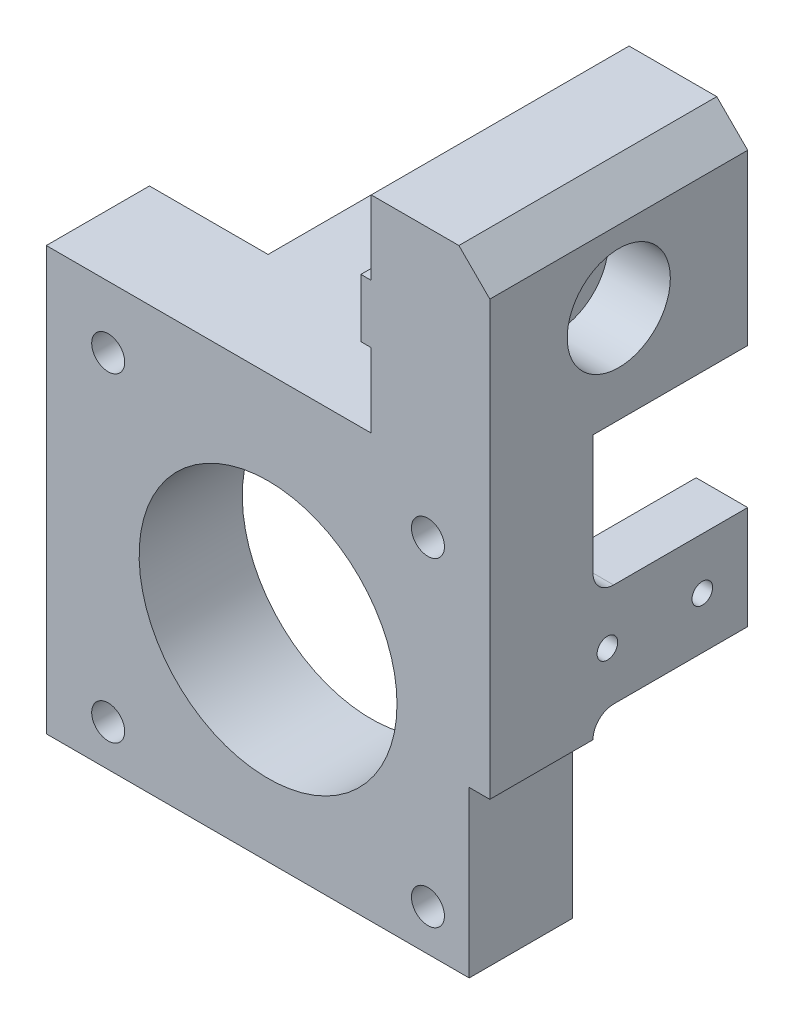
SolidWorks part; units mm, degrees
ref_plane "Plano frontal" through (0, 0, 0) normal (0, 0, 1) x (1, 0, 0)
ref_plane "Plano superior" through (0, 0, 0) normal (0, 1, 0) x (1, 0, 0)
ref_plane "Plano direito" through (0, 0, 0) normal (1, 0, 0) x (0, 0, -1)
sketch "Esboço1" plane through (0, 0, 0) normal (0, 0, 1) x (1, 0, 0)
  line L0 (-21.5, 21.5) -> (-21.5, -21.5)
  line L1 (-21.5, -21.5) -> (21.5, -21.5)
  line L2 (21.5, -21.5) -> (21.5, 38.5)
  line L3 (21.5, 38.5) -> (18.5, 41.5)
  line L4 (18.5, 41.5) -> (10, 41.5)
  line L5 (10, 41.5) -> (10, 34.325)
  line L6 (10, 34.325) -> (9, 34.325)
  line L7 (9, 34.325) -> (9, 28.675)
  line L8 (9, 28.675) -> (10, 28.675)
  line L9 (10, 28.675) -> (10, 21.5)
  line L10 (10, 21.5) -> (-21.5, 21.5)
  line L11 (0, -21.5) -> (0, 0) construction
  line L12 (-21.5, 0) -> (0, 0) construction
  line L13 (9, 31.5) -> (21.5, 31.5) construction
  line L14 (14.25, 41.5) -> (14.25, 21.5) construction
  line L15 (10, 21.5) -> (21.5, 21.5) construction
  line L17 (15.5, -15.5) -> (-15.5, -15.5) construction
  line L18 (15.5, -15.5) -> (15.5, 15.5) construction
  line L19 (15.5, 15.5) -> (-15.5, 15.5) construction
  line L20 (-15.5, -15.5) -> (-15.5, 15.5) construction
  line L21 (15.5, -15.5) -> (-15.5, 15.5) construction
  line L22 (15.5, 15.5) -> (-15.5, -15.5) construction
  circle A0 centre (0, 0) radius 12.5
  circle A1 centre (-15.5, 15.5) radius 1.6
  circle A2 centre (15.5, 15.5) radius 1.6
  circle A3 centre (15.5, -15.5) radius 1.6
  circle A4 centre (-15.5, -15.5) radius 1.6
  point P20 (14.25, 31.5)
  dimension "D10" = 25
  dimension "D9" = 3.2
  dimension "D1" = 43
  dimension "D2" = 43
  dimension "D3" = 60
  dimension "D4" = 11.5
  dimension "D5" = 135
  dimension "D6" = 20
  dimension "D7" = 5.65
  dimension "D8" = 1
  dimension "D11" = 31
  dimension "D12" = 31
extrude "Ressalto-extrusão1" add sketch "Esboço1" along normal blind 10
sketch "Esboço3" plane through (0, 0, 0) normal (0, 0, -1) x (-1, 0, 0)
  circle A0 centre (-15.5, 15.5) radius 3.6
  circle A1 centre (15.5, 15.5) radius 3.6
  circle A2 centre (15.5, -15.5) radius 3.6
  circle A3 centre (-15.5, -15.5) radius 3.6
  dimension "D1" = 7.2
extrude "Corte-extrusão1" cut sketch "Esboço3" against normal blind 3
sketch "Esboço2" plane through (0, 0, 0) normal (0, 0, -1) x (-1, 0, 0)
  line L0 (-18.5, 41.5) -> (-21.5, 38.5)
  line L1 (-21.5, 38.5) -> (-21.5, 22.1)
  line L4 (10, 15.5) -> (10, 21.5)
  line L5 (-10, 21.5) -> (21.5, 21.5) construction
  line L6 (10, 21.5) -> (-10, 21.5)
  line L7 (-10, 21.5) -> (-10, 28.675)
  line L8 (-10, 28.675) -> (-9, 28.675)
  line L9 (-9, 28.675) -> (-9, 34.325)
  line L10 (-9, 34.325) -> (-10, 34.325)
  line L11 (-10, 34.325) -> (-10, 41.5)
  line L12 (-10, 41.5) -> (-18.5, 41.5)
  line L13 (7, 12.5) -> (10, 15.5)
  line L14 (-10.9, 12.5) -> (7, 12.5)
  line L15 (-21.5, 22.1) -> (-18.5, 19.1)
  line L16 (-18.5, 19.1) -> (-15.5, 19.1)
  line L17 (-11.9, 15.5) -> (-11.9, 13.5)
  line L18 (-11.9, 13.5) -> (-10.9, 12.5)
  circle A1 centre (-15.5, 15.5) radius 3.6 construction
  arc A2 (-11.9, 15.5) -> (-15.5, 19.1) centre (-15.5, 15.5) ccw
  circle A3 centre (0, 0) radius 12.5 construction
  point P8 (10, 12.5)
  point P35 (-11.9, 12.5)
  line M12 (21.5, 21.5) -> (-10, 21.5)
  line M13 (-10, 21.5) -> (-10, 28.675)
  line M14 (-10, 28.675) -> (-9, 28.675)
  line M15 (-9, 28.675) -> (-9, 34.325)
  line M16 (-9, 34.325) -> (-10, 34.325)
  line M17 (-10, 34.325) -> (-10, 41.5)
  line M18 (-10, 41.5) -> (-18.5, 41.5)
  line M19 (-18.5, 41.5) -> (-21.5, 38.5)
  line M20 (-21.5, 38.5) -> (-21.5, -21.5)
  circle M34 centre (-15.5, 15.5) radius 3.6
  dimension "D1" = 31.5
  dimension "D2" = 3
  dimension "D4" = 3
extrude "Ressalto-extrusão2" add sketch "Esboço2" along normal blind 15 contours L15 L16 L14 L13 L4 M34 M12 M13 M14 M15 M16 M17 M18 M19 M20
sketch "Esboço4" plane through (21.5, 0, 0) normal (1, 0, 0) x (0, 0, -1)
  line L0 (-10, 41.5) -> (15, 41.5) construction
  line L4 (2.5, 41.5) -> (2.5, 19.1) construction
  line L5 (15, 19.1) -> (0, 19.1) construction
  circle A0 centre (2.5, 31.5) radius 2.25
  dimension "D1" = 4.5
  dimension "D2" = 10
extrude "Corte-extrusão2" cut sketch "Esboço4" against normal through all
sketch "Esboço5" plane through (0, 21.5, 0) normal (0, 1, 0) x (1, 0, 0)
  line L0 (-10, 7.5) -> (9, 7.5) construction
  line L1 (-10, 15) -> (-10, 0) construction
  line L2 (9, -10) -> (9, 15) construction
  line L3 (0, 15) -> (0, -10) construction
  line L4 (-10, 15) -> (10, 15) construction
  line L5 (10, -10) -> (-21.5, -10) construction
  circle A0 centre (0, 7.5) radius 2.25
  dimension "D1" = 4.5
extrude "Corte-extrusão3" cut sketch "Esboço5" against normal through all
sketch "Esboço6" plane through (0, 12.5, 0) normal (0, -1, 0) x (1, 0, 0)
  circle A0 centre (0, -7.5) radius 5
  dimension "D1" = 10
extrude "Corte-extrusão4" cut sketch "Esboço6" against normal blind 3.5
sketch "Esboço7" plane through (21.5, 0, 0) normal (1, 0, 0) x (0, 0, -1)
  circle A0 centre (2.5, 31.5) radius 5
  dimension "D1" = 10
extrude "Corte-extrusão5" cut sketch "Esboço7" against normal blind 6
sketch "Esboço8" plane through (21.5, 0, 0) normal (1, 0, 0) x (0, 0, -1)
  line L0 (0, 8.5) -> (15, 8.5)
  line L1 (0, -21.5) -> (0, 22.1) construction
  line L2 (1.4, 3.5) -> (10.6, 3.5) construction
  line L3 (6, 8.5) -> (6, 3.5) construction
  line L4 (15, 8.5) -> (15, -1.5)
  line L5 (15, -1.5) -> (0, -1.5)
  line L7 (-10, -21.5) -> (0, -21.5) construction
  line L8 (15, 38.5) -> (15, 22.1) construction
  line L9 (0, 8.5) -> (-2, 8.5)
  line L10 (-2, 8.5) -> (-2, -1.5)
  line L11 (-2, -1.5) -> (0, -1.5)
  circle A0 centre (1.4, 3.5) radius 1
  circle A1 centre (10.6, 3.5) radius 1
  point P10 (15, 3.5)
  dimension "D1" = 2
  dimension "D2" = 9.2
  dimension "D3" = 5
  dimension "D4" = 10
  dimension "D5" = 20
  dimension "D6" = 6
  dimension "D7" = 2
extrude "Ressalto-extrusão3" add sketch "Esboço8" against normal blind 5
sketch "Esboço9" plane through (16.5, 0, 0) normal (-1, 0, 0) x (0, 0, 1)
  line L1 (-9.0989, 0.9) -> (-7.5978, 3.5)
  line L2 (-7.5978, 3.5) -> (-9.0989, 6.1)
  line L3 (-9.0989, 6.1) -> (-12.1011, 6.1)
  line L4 (-12.1011, 6.1) -> (-13.6022, 3.5)
  line L5 (-13.6022, 3.5) -> (-12.1011, 0.9)
  line L6 (-12.1011, 0.9) -> (-9.0989, 0.9)
  line L7 (-4.4022, 3.5) -> (-2.9011, 0.9)
  line L8 (-2.9011, 0.9) -> (0.1011, 0.9)
  line L9 (0.1011, 0.9) -> (1.6022, 3.5)
  line L10 (1.6022, 3.5) -> (0.1011, 6.1)
  line L11 (0.1011, 6.1) -> (-2.9011, 6.1)
  line L12 (-2.9011, 6.1) -> (-4.4022, 3.5)
  circle A0 centre (-10.6, 3.5) radius 2.6 construction
  circle A1 centre (-1.4, 3.5) radius 2.6 construction
  dimension "D1" = 5.2
extrude "Corte-extrusão7" cut sketch "Esboço9" against normal blind 2 and the other way blind 10
fillet "Filete1" radius 2 4 edges at (19, 8.5, 0) (19, -1.5, 0) (16.5, 7.3, 0) (16.5, -0.3, 0)
sketch "Esboço10" plane through (0, 0, 0) normal (0, 0, -1) x (-1, 0, 0)
  line L0 (-21.5, -3.5) -> (-19.5, -3.5)
  line L1 (-14.5, -3.5) -> (-21.5, -3.5) construction
  line L2 (-19.5, -3.5) -> (-19.5, -19.5)
  line L3 (21.5, -21.5) -> (-21.5, -21.5) construction
  line L4 (-19.5, -21.5) -> (-21.5, -21.5)
  line L5 (-21.5, -21.5) -> (-21.5, -3.5)
  line L6 (-19.5, -21.5) -> (21.5, -21.5)
  line L7 (21.5, -21.5) -> (21.5, -19.5)
  line L8 (21.5, 21.5) -> (21.5, -21.5) construction
  line L9 (21.5, -19.5) -> (-19.5, -19.5)
  dimension "D1" = 2
  dimension "D2" = 2
extrude "Corte-extrusão8" cut sketch "Esboço10" against normal through all both and the other way through all
